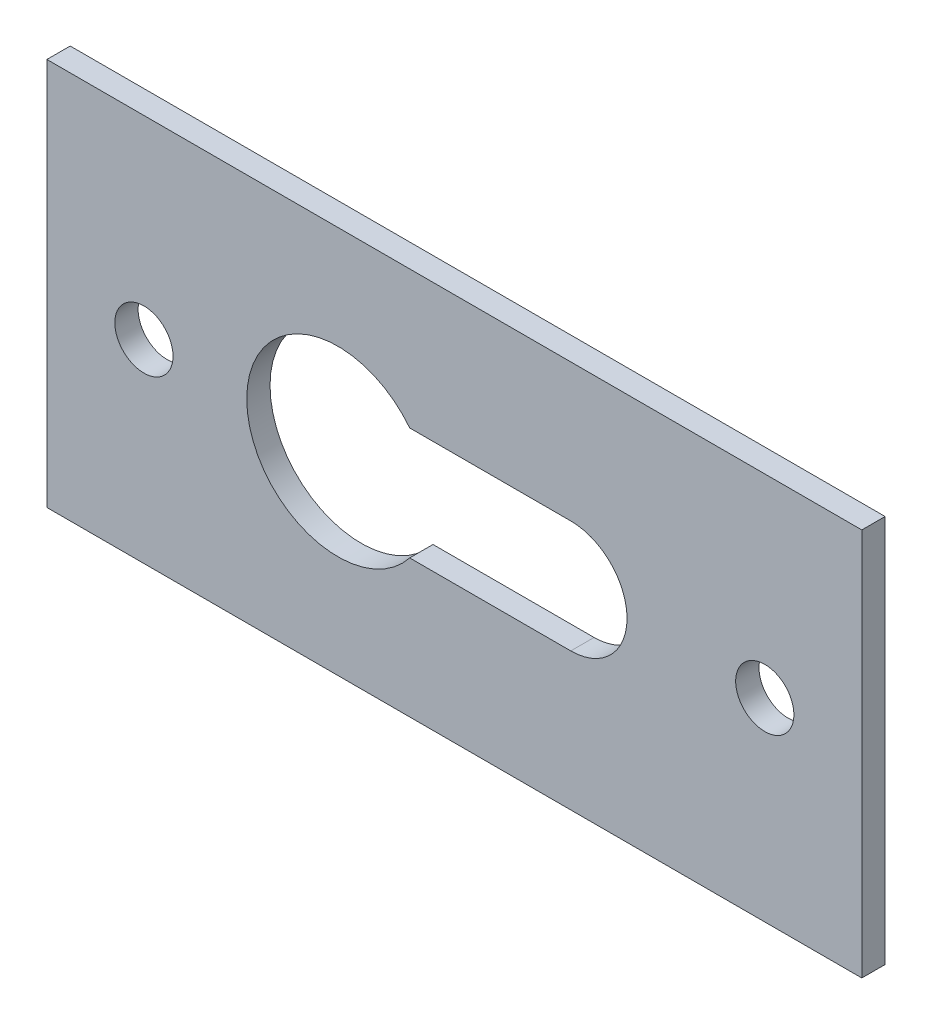
SolidWorks part; units mm, degrees
ref_plane "Plan de face" through (0, 0, 0) normal (0, 0, 1) x (1, 0, 0)
ref_plane "Plan de dessus" through (0, 0, 0) normal (0, 1, 0) x (1, 0, 0)
ref_plane "Plan de droite" through (0, 0, 0) normal (1, 0, 0) x (0, 0, -1)
sketch "Esquisse1" plane through (0, 0, 0) normal (0, 0, 1) x (1, 0, 0)
  line L0 (0, 0) -> (68.4105, 0) construction
  line L1 (27, 2.9) -> (18.6986, 2.9)
  line L2 (0, 10) -> (42, 10)
  line L3 (0, 10) -> (0, -10)
  line L4 (0, -10) -> (42, -10)
  line L5 (42, 10) -> (42, -10)
  line L7 (27, -2.9) -> (18.6986, -2.9)
  arc A0 (18.6986, 2.9) -> (18.6986, -2.9) centre (15, 0) ccw
  arc A1 (27, -2.9) -> (27, 2.9) centre (27, 0) ccw
  circle A2 centre (37, 0) radius 1.5
  circle A3 centre (5, 0) radius 1.5
  dimension "D1" = 9.4
  dimension "D2" = 5.8
  dimension "D7" = 5
  dimension "D8" = 3
  dimension "D3" = 12
  dimension "D4" = 20
  dimension "D5" = 15
  dimension "D6" = 15
  dimension "D9" = 5
extrude "Boss.-Extru.1" add sketch "Esquisse1" along normal blind 1.2
